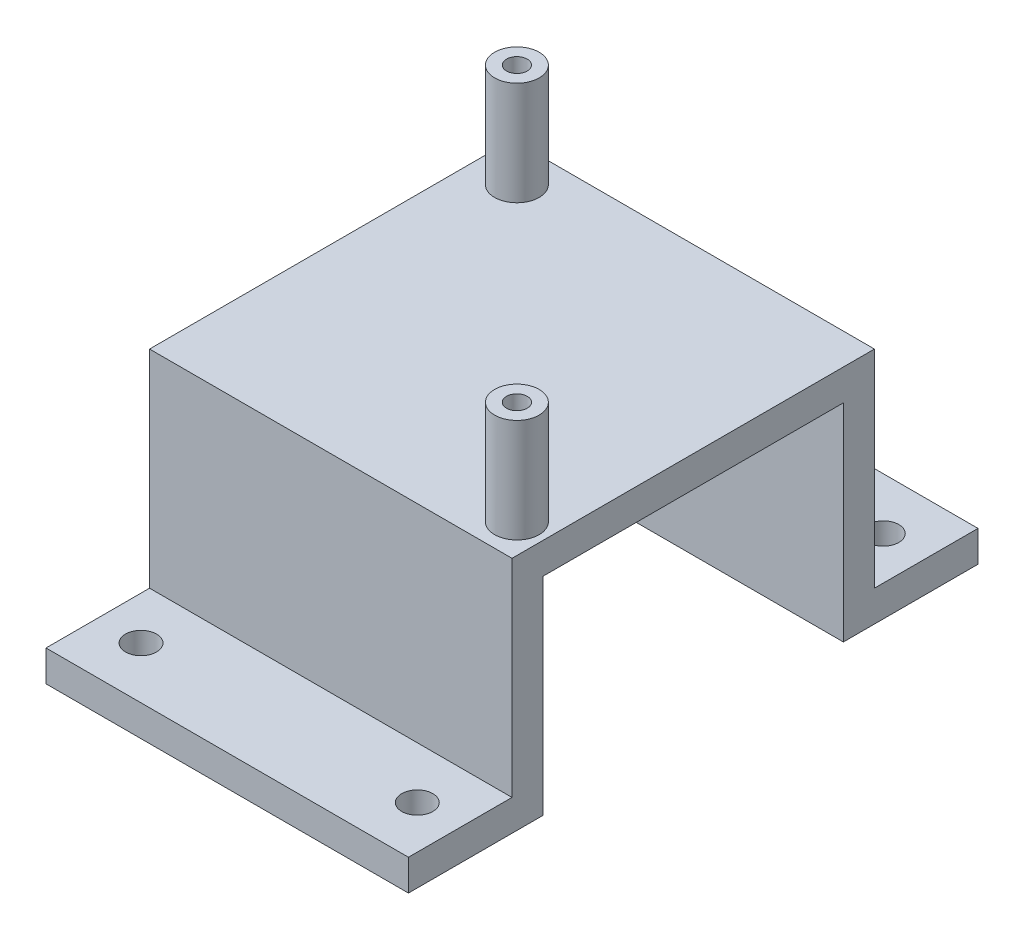
SolidWorks part; units mm, degrees
ref_plane "Front Plane" through (0, 0, 0) normal (0, 0, 1) x (1, 0, 0)
ref_plane "Top Plane" through (0, 0, 0) normal (0, 1, 0) x (1, 0, 0)
ref_plane "Right Plane" through (0, 0, 0) normal (1, 0, 0) x (0, 0, -1)
sketch "Sketch1" plane through (0, 0, 0) normal (0, 1, 0) x (1, 0, 0)
  line L1 (-17.5, -17.5) -> (17.5, -17.5)
  line L2 (-17.5, -17.5) -> (-17.5, 17.5)
  line L3 (-17.5, 17.5) -> (17.5, 17.5)
  line L4 (17.5, -17.5) -> (17.5, 17.5)
  line L5 (-17.5, -17.5) -> (17.5, 17.5) construction
  line L6 (-17.5, 17.5) -> (17.5, -17.5) construction
  point P0 (0, 0)
  dimension "D1" = 35
  dimension "D2" = 35
extrude "Boss-Extrude1" add sketch "Sketch1" along normal blind 3
sketch "Sketch2" plane through (0, 3, 0) normal (0, 1, 0) x (1, 0, 0)
  circle A0 centre (-13.5127, 13.9848) radius 2.15
  circle A1 centre (14.6873, -14.2152) radius 2.15
  circle A2 centre (-13.5127, 13.9848) radius 1
  circle A3 centre (14.6873, -14.2152) radius 1
  dimension "D1" = 4.3
  dimension "D2" = 4.3
  dimension "D5" = 2
  dimension "D6" = 2
  dimension "D3" = 28.2
  dimension "D4" = 28.2
extrude "Boss-Extrude2" add sketch "Sketch2" along normal blind 10
sketch "Sketch3" plane through (0, 0, 0) normal (0, -1, 0) x (1, 0, 0)
  line L0 (17.5, 17.5) -> (17.5, -17.5) construction
  line L1 (-17.5, 17.5) -> (17.5, 17.5)
  line L2 (-17.5, 17.5) -> (-17.5, 14.5)
  line L3 (-17.5, 14.5) -> (17.5, 14.5)
  line L4 (17.5, 17.5) -> (17.5, 14.5)
  line L5 (-17.5, -17.5) -> (-17.5, 17.5) construction
  line L6 (17.5, -17.5) -> (-17.5, -17.5)
  line L7 (17.5, -17.5) -> (17.5, -14.5)
  line L8 (17.5, -14.5) -> (-17.5, -14.5)
  line L9 (-17.5, -17.5) -> (-17.5, -14.5)
  dimension "D1" = 3
  dimension "D2" = 3
extrude "Boss-Extrude3" add sketch "Sketch3" along normal blind 20
sketch "Sketch4" plane through (0, 0, -17.5) normal (0, 0, -1) x (-1, 0, 0)
  line L0 (-17.5, 3) -> (-17.5, -20) construction
  line L1 (17.5, -20) -> (-17.5, -20)
  line L2 (17.5, -20) -> (17.5, -17)
  line L3 (17.5, -17) -> (-17.5, -17)
  line L4 (-17.5, -20) -> (-17.5, -17)
  dimension "D1" = 3
extrude "Boss-Extrude4" add sketch "Sketch4" along normal blind 10
sketch "Sketch5" plane through (0, -17, 0) normal (0, 1, 0) x (1, 0, 0)
  line L1 (-13.3246, 27.5) -> (-13.3246, 17.5) construction
  line L2 (-17.5, 27.5) -> (17.5, 27.5) construction
  line L3 (-17.5, 17.5) -> (17.5, 17.5) construction
  line L4 (13.3553, 27.5) -> (13.3553, 17.5) construction
  line L5 (17.5, 17.5) -> (-17.5, 17.5) construction
  circle A0 centre (-13.3246, 22.5) radius 1.5
  circle A1 centre (13.3553, 22.5) radius 1.5
  point P8 (14.3661, 20.913)
  dimension "D1" = 3
  dimension "D2" = 3
extrude "Cut-Extrude1" cut sketch "Sketch5" against normal blind 10
mirror "Mirror1" about plane through (0, 0, 0) normal (0, 0, 1) of "Boss-Extrude4", "Cut-Extrude1"
